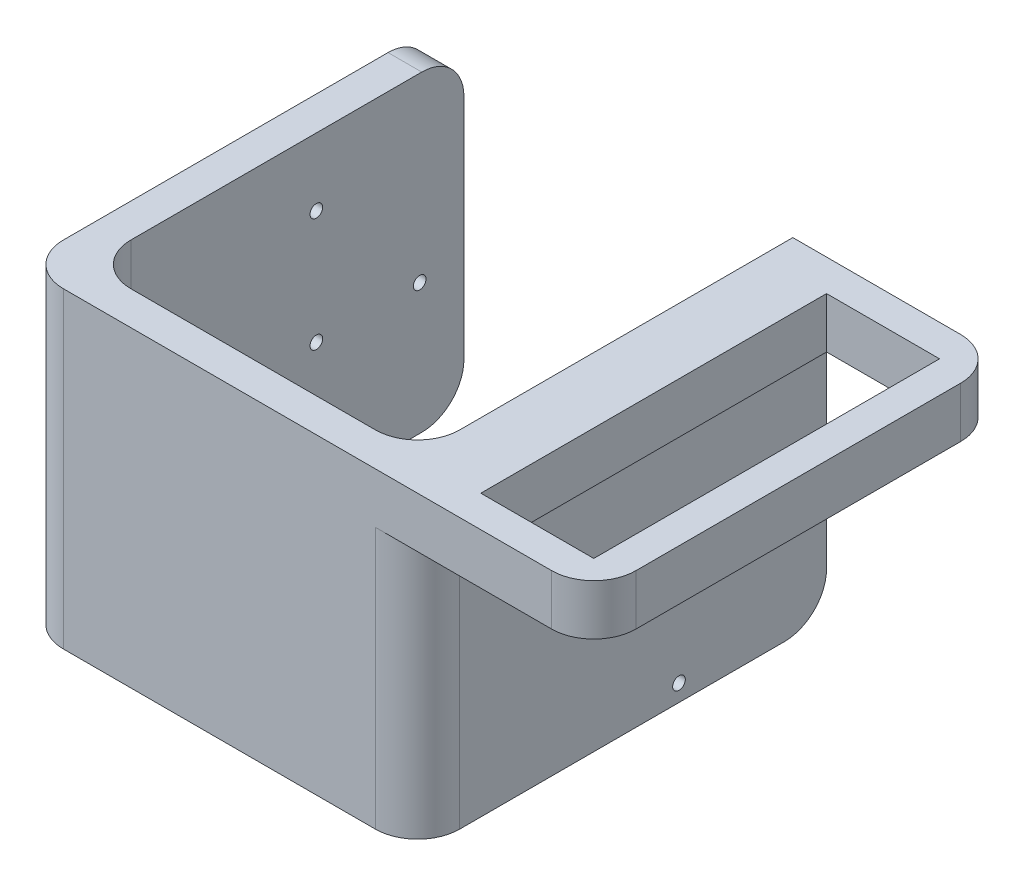
SolidWorks part; units mm, degrees
ref_plane "Front Plane" through (0, 0, 0) normal (0, 0, 1) x (1, 0, 0)
ref_plane "Top Plane" through (0, 0, 0) normal (0, 1, 0) x (1, 0, 0)
ref_plane "Right Plane" through (0, 0, 0) normal (1, 0, 0) x (0, 0, -1)
sketch "Sketch1" plane through (0, 0, 0) normal (0, 0, 1) x (1, 0, 0)
  line L1 (-47, 37) -> (47, 37)
  line L2 (-47, 37) -> (-47, -37)
  line L3 (-47, -37) -> (47, -37)
  line L4 (47, 37) -> (47, -37)
  line L5 (-47, 37) -> (47, -37) construction
  line L6 (-47, -37) -> (47, 37) construction
  point P0 (0, 0)
  dimension "D1" = 94
  dimension "D2" = 74
extrude "Boss-Extrude1" add sketch "Sketch1" along normal blind 8
sketch "Sketch3" plane through (0, 0, 0) normal (0, 0, -1) x (-1, 0, 0)
  line L0 (-47, 37) -> (47, 37) construction
  line L1 (39, 37) -> (47, 37)
  line L2 (39, 37) -> (39, -37)
  line L3 (39, -37) -> (47, -37)
  line L4 (47, 37) -> (47, -37)
  line L5 (39, 37) -> (47, -37) construction
  line L6 (39, -37) -> (47, 37) construction
  point P4 (43, 0)
  dimension "D1" = 8
extrude "Boss-Extrude2" add sketch "Sketch3" along normal blind 89
sketch "Sketch4" plane through (0, 0, 0) normal (0, 0, -1) x (-1, 0, 0)
  line L0 (39, -37) -> (-47, -37) construction
  line L1 (-47, 37) -> (-39, 37)
  line L2 (-47, 37) -> (-47, -37)
  line L3 (-47, -37) -> (-39, -37)
  line L4 (-39, 37) -> (-39, -37)
  line L5 (-47, 37) -> (-39, -37) construction
  line L6 (-47, -37) -> (-39, 37) construction
  point P4 (-43, 0)
  dimension "D1" = 8
extrude "Boss-Extrude3" add sketch "Sketch4" along normal blind 89
sketch "Sketch7" plane through (47, 0, 0) normal (1, 0, 0) x (0, 0, -1)
  line L0 (89, 37) -> (89, -37) construction
  line L1 (-8, 37) -> (89, 37)
  line L2 (-8, 37) -> (-8, 25)
  line L3 (-8, 25) -> (89, 25)
  line L4 (89, 37) -> (89, 25)
  line L5 (-8, 37) -> (89, 25) construction
  line L6 (-8, 25) -> (89, 37) construction
  point P4 (40.5, 31)
  dimension "D1" = 12
extrude "Boss-Extrude6" add sketch "Sketch7" along normal blind 41.8
sketch "Sketch12" plane through (0, 25, 0) normal (0, -1, 0) x (1, 0, 0)
  line L1 (47, 8) -> (88.8, 8)
  line L2 (47, 8) -> (47, -89)
  line L3 (47, -89) -> (88.8, -89)
  line L4 (88.8, 8) -> (88.8, -89)
  line L5 (47, 8) -> (88.8, -89) construction
  line L6 (47, -89) -> (88.8, 8) construction
  point P4 (67.9, -40.5)
sketch "Sketch13" plane through (0, 25, 0) normal (0, -1, 0) x (1, 0, 0)
  line L1 (54.5, 0.5) -> (81.3, 0.5)
  line L2 (54.5, 0.5) -> (54.5, -81.5)
  line L3 (54.5, -81.5) -> (81.3, -81.5)
  line L4 (81.3, 0.5) -> (81.3, -81.5)
  line L5 (54.5, 0.5) -> (81.3, -81.5) construction
  line L6 (54.5, -81.5) -> (81.3, 0.5) construction
  point P0 (67.9, -40.5)
  dimension "D1" = 26.8
  dimension "D2" = 82
extrude "Cut-Extrude3" cut sketch "Sketch13" against normal blind 15
sketch "Sketch17" plane through (47, 0, 0) normal (1, 0, 0) x (0, 0, -1)
  line L0 (89, 25) -> (89, -6)
  line L1 (89, 25) -> (89, -37) construction
  line L2 (89, -6) -> (54, -6)
  line L4 (29.5, 21) -> (78.5, 21)
  line L5 (29.5, 21) -> (29.5, -33)
  line L6 (29.5, -33) -> (78.5, -33)
  line L7 (78.5, 21) -> (78.5, -33)
  line L8 (29.5, 21) -> (78.5, -33) construction
  line L9 (29.5, -33) -> (78.5, 21) construction
  dimension "D1" = 35
  dimension "D2" = 49
  dimension "D3" = 54
sketch "Sketch18" plane through (47, 0, 0) normal (1, 0, 0) x (0, 0, -1)
  line L1 (29.5, 21) -> (54, 21)
  line L2 (29.5, 21) -> (29.5, -6)
  line L3 (29.5, -6) -> (54, -6)
  line L4 (54, 21) -> (54, -6)
  line L5 (29.5, 21) -> (54, -6) construction
  line L6 (29.5, -6) -> (54, 21) construction
  point P4 (41.75, 7.5)
sketch "Sketch19" plane through (47, 0, 0) normal (1, 0, 0) x (0, 0, -1)
  line L0 (78.5, 21) -> (78.5, -33) construction
  line L1 (29.5, -33) -> (78.5, -33) construction
  circle A0 centre (54, 21) radius 1.5
  circle A1 centre (29.5, -6) radius 1.5
  circle A2 centre (78.5, -6) radius 1.5
  circle A3 centre (54, -33) radius 1.5
  circle A4 centre (54, -6) radius 1.5
  dimension "D1" = 3
sketch "Sketch20" plane through (47, 0, 0) normal (1, 0, 0) x (0, 0, -1)
  line L0 (29.5, -33) -> (78.5, -33) construction
  line L1 (29.5, -6) -> (54, -6)
  line L2 (29.5, -6) -> (29.5, -33)
  line L3 (29.5, -33) -> (54, -33)
  line L4 (54, -6) -> (54, -33)
  line L5 (29.5, -6) -> (54, -33) construction
  line L6 (29.5, -33) -> (54, -6) construction
  point P4 (41.75, -19.5)
extrude "Cut-Extrude4" cut sketch "Sketch19" against normal blind 100
fillet "Fillet1" radius 10 2 edges at (-43, 37, -89)
fillet "Fillet2" radius 10 1 edges at (-43, -37, -89)
fillet "Fillet3" radius 10 1 edges at (43, -37, -89)
fillet "Fillet4" radius 10 1 edges at (-47, 0, 8)
fillet "Fillet5" radius 10 1 edges at (88.8, 31, 8)
fillet "Fillet6" radius 10 1 edges at (88.8, 31, -89)
fillet "Fillet7" radius 10 1 edges
fillet "Fillet8" radius 10 1 edges at (39, 0, 0)
